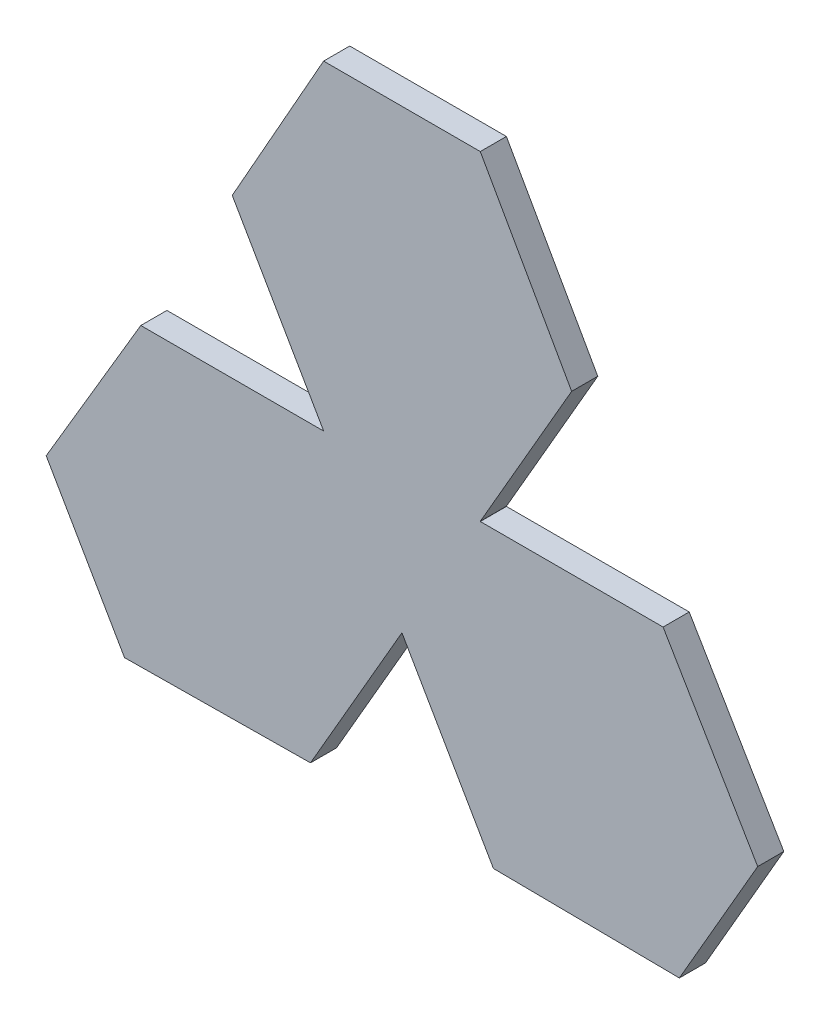
SolidWorks part; units mm, degrees
ref_plane "Front Plane" through (0, 0, 0) normal (0, 0, 1) x (1, 0, 0)
ref_plane "Top Plane" through (0, 0, 0) normal (0, 1, 0) x (1, 0, 0)
ref_plane "Right Plane" through (0, 0, 0) normal (1, 0, 0) x (0, 0, -1)
sketch "Sketch1" plane through (0, 0, 0) normal (0, 0, 1) x (1, 0, 0)
  line L0 (0, 17.3205) -> (0, 70) construction
  line L1 (15, 8.6603) -> (10, 17.3205) construction
  line L2 (0, 17.3205) -> (-10, 17.3205) construction
  line L3 (-15, 8.6603) -> (-20, 0) construction
  line L4 (-20, 0) -> (-15, -8.6603) construction
  line L5 (-10, -17.3205) -> (0, -17.3205) construction
  line L6 (15, -8.6603) -> (20, 0) construction
  line L7 (80.829, 0) -> (40.4145, 70) construction
  line L8 (40.4145, 70) -> (-40.4145, 70) construction
  line L9 (-40.4145, 70) -> (-80.829, 0) construction
  line L10 (-80.829, 0) -> (-40.4145, -70) construction
  line L11 (-40.4145, -70) -> (40.4145, -70) construction
  line L12 (40.4145, -70) -> (80.829, 0) construction
  line L14 (-32.495, 38.9798) -> (-15, 70)
  line L18 (10, 17.3205) -> (0, 17.3205) construction
  line L19 (-15, -8.6603) -> (-10, -17.3205) construction
  line L20 (10, -17.3205) -> (15, -8.6603) construction
  line L21 (-10, 17.3205) -> (-15, 8.6603) construction
  line L22 (20, 0) -> (15, 8.6603) construction
  line L23 (0, -17.3205) -> (10, -17.3205) construction
  line L24 (-10, 17.3205) -> (-14.995, 8.6689) construction
  line L25 (-15, 8.6603) -> (-14.995, 8.6689)
  line L26 (-14.995, 8.6689) -> (-32.495, 38.9798)
  line L27 (15, 70) -> (-15, 70)
  line L28 (32.495, 38.9798) -> (15, 70)
  line L29 (14.995, 8.6689) -> (32.495, 38.9798)
  line L30 (15, 8.6603) -> (14.995, 8.6689)
  line L31 (15, 8.6603) -> (15.005, 8.6516)
  line L32 (15.005, 8.6516) -> (50.005, 8.6516)
  line L33 (50.005, 8.6516) -> (68.1218, -22.0096)
  line L34 (53.1218, -47.9904) -> (68.1218, -22.0096)
  line L35 (17.51, -47.6314) -> (53.1218, -47.9904)
  line L36 (0.01, -17.3205) -> (17.51, -47.6314)
  line L37 (0, -17.3205) -> (0.01, -17.3205)
  line L38 (0, -17.3205) -> (-0.01, -17.3205)
  line L39 (-0.01, -17.3205) -> (-17.51, -47.6314)
  line L40 (-17.51, -47.6314) -> (-53.1218, -47.9904)
  line L41 (-68.1218, -22.0096) -> (-53.1218, -47.9904)
  line L42 (-50.005, 8.6516) -> (-68.1218, -22.0096)
  line L43 (-15.005, 8.6516) -> (-50.005, 8.6516)
  line L44 (-15, 8.6603) -> (-15.005, 8.6516)
  arc A0 (15, 8.6603) -> (0, 17.3205) centre (0, 0) ccw construction
  circle A1 centre (0, 0) radius 70 construction
  arc A2 (15, -8.6603) -> (15, 8.6603) centre (0, 0) ccw construction
  arc A3 (0, -17.3205) -> (15, -8.6603) centre (0, 0) ccw construction
  arc A4 (0, 17.3205) -> (-15, 8.6603) centre (0, 0) ccw construction
  arc A5 (-15, -8.6603) -> (0, -17.3205) centre (0, 0) ccw construction
  arc A6 (-15, 8.6603) -> (-15, -8.6603) centre (0, 0) ccw construction
  point P47 (0, 0)
  dimension "D1" = 20
  dimension "D2" = 140
  dimension "D3" = 15
  dimension "D4" = 9.99
  dimension "D5" = 35
  dimension "D6" = 120
  dimension "D7" = 3
extrude "Boss-Extrude1" add sketch "Sketch1" along normal blind 5
